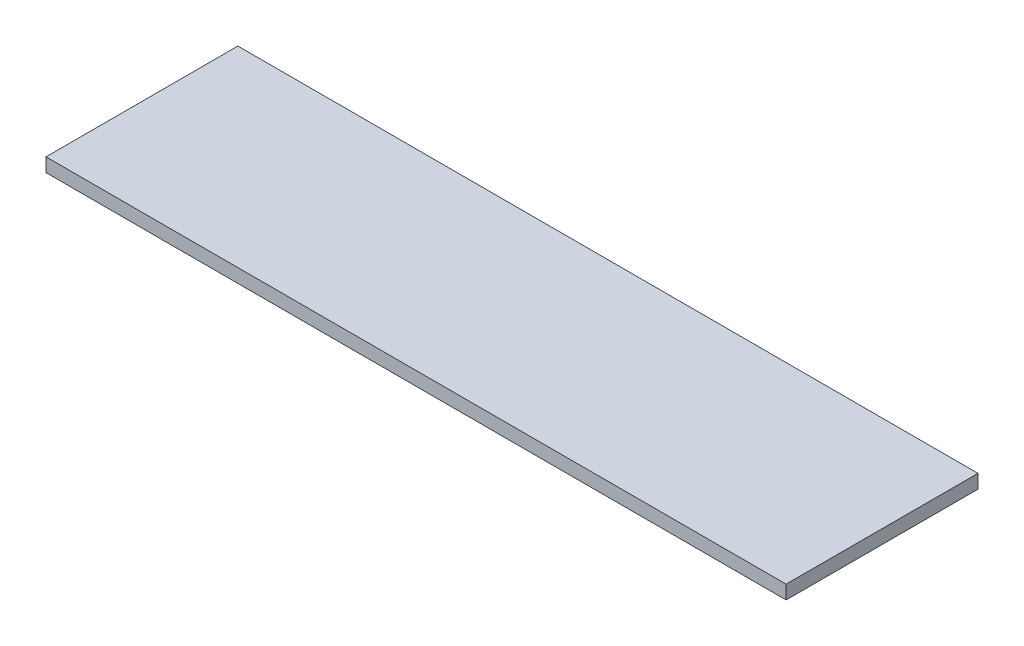
SolidWorks part; units mm, degrees
ref_plane "Front Plane" through (0, 0, 0) normal (0, 0, 1) x (1, 0, 0)
ref_plane "Top Plane" through (0, 0, 0) normal (0, 1, 0) x (1, 0, 0)
ref_plane "Right Plane" through (0, 0, 0) normal (1, 0, 0) x (0, 0, -1)
sketch "Sketch1" plane through (0, 0, 0) normal (0, 1, 0) x (1, 0, 0)
  line L1 (-81, 21) -> (81, 21)
  line L2 (-81, 21) -> (-81, -21)
  line L3 (-81, -21) -> (81, -21)
  line L4 (81, 21) -> (81, -21)
  line L5 (-81, 21) -> (81, -21) construction
  line L6 (-81, -21) -> (81, 21) construction
  point P0 (0, 0)
extrude "Boss-Extrude1" add sketch "Sketch1" along normal blind 3
